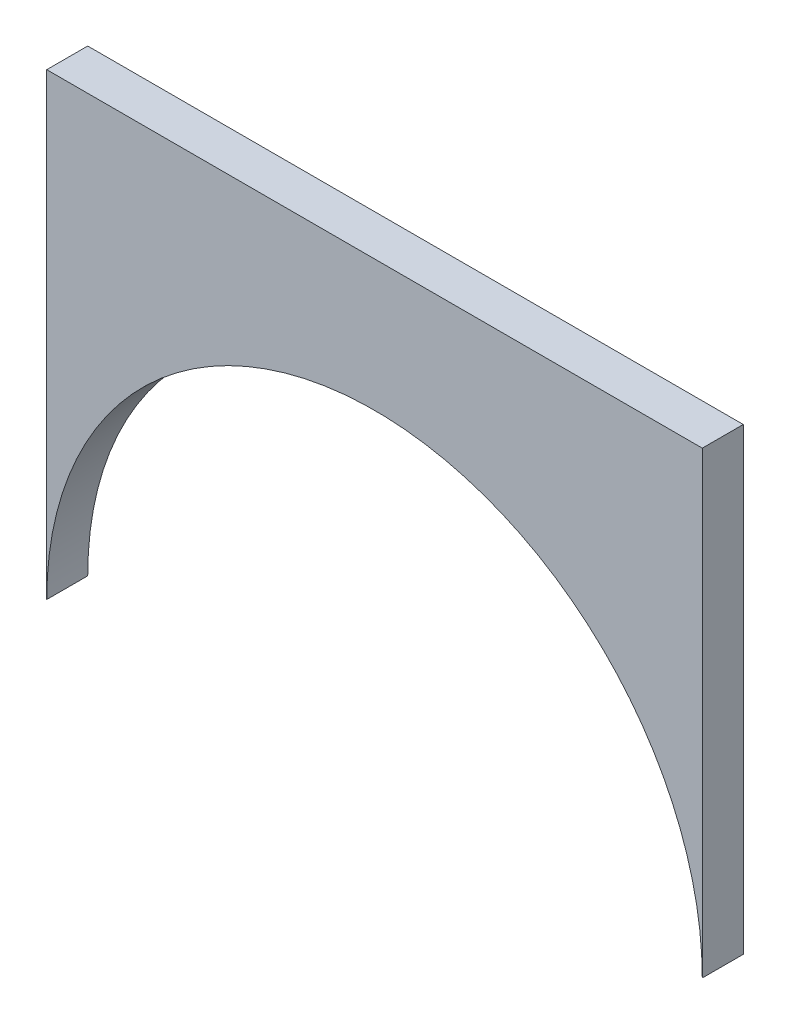
SolidWorks part; units mm, degrees
ref_plane "정면" through (0, 0, 0) normal (0, 0, 1) x (1, 0, 0)
ref_plane "윗면" through (0, 0, 0) normal (0, 1, 0) x (1, 0, 0)
ref_plane "우측면" through (0, 0, 0) normal (1, 0, 0) x (0, 0, -1)
sketch "스케치1" plane through (0, 0, 0) normal (0, 0, 1) x (1, 0, 0)
  line L0 (-20, 0) -> (-20, 28)
  line L1 (-20, 28) -> (20, 28)
  line L2 (20, 28) -> (20, 0)
  arc A0 (-20, 0) -> (20, 0) centre (0, 0) cw
  dimension "D1" = 20
  dimension "D2" = 28
extrude "보스-돌출1" add sketch "스케치1" along normal blind 2.5
